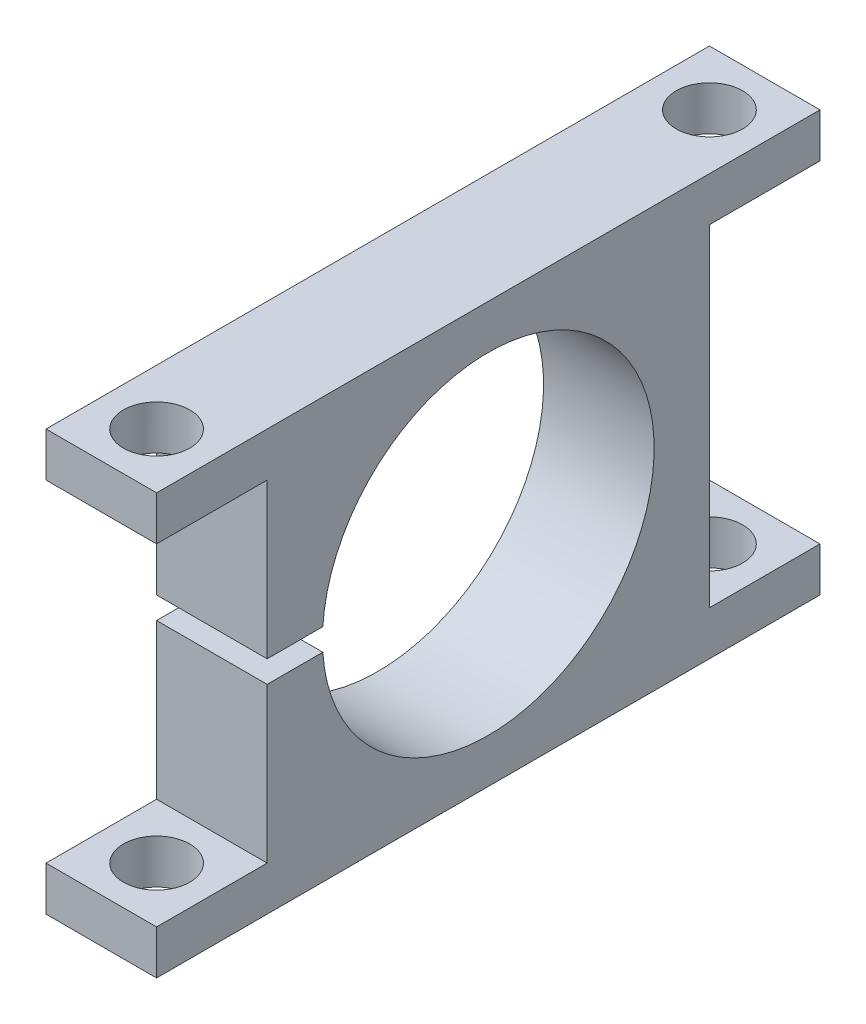
SolidWorks part; units mm, degrees
ref_plane "前视基准面" through (0, 0, 0) normal (0, 0, 1) x (1, 0, 0)
ref_plane "上视基准面" through (0, 0, 0) normal (0, 1, 0) x (1, 0, 0)
ref_plane "右视基准面" through (0, 0, 0) normal (1, 0, 0) x (0, 0, -1)
sketch "草图1" plane through (0, 0, 0) normal (1, 0, 0) x (0, 0, -1)
  line L1 (-10, -9.5) -> (10, -9.5)
  line L2 (10, -9.5) -> (10, 9.5)
  line L3 (10, 9.5) -> (-10, 9.5)
  line L4 (-10, -9.5) -> (-10, 9.5)
  line L5 (10, -9.5) -> (-10, 9.5) construction
  line L6 (10, 9.5) -> (-10, -9.5) construction
  circle A0 centre (0, 0) radius 7.5
  dimension "D1" = 20
  dimension "D2" = 15
  dimension "D3" = 19
extrude "凸台-拉伸3" add sketch "草图1" along normal blind 5
sketch "草图3" plane through (0, 0, 0) normal (-1, 0, 0) x (0, 0, 1)
  line L0 (10, 9.5) -> (15, 9.5)
  line L1 (15, 9.5) -> (15, 7.5)
  line L2 (15, 7.5) -> (10, 7.5)
  line L3 (10, 9.5) -> (10, -9.5) construction
  line L4 (10, 7.5) -> (10, 9.5)
  line L5 (10, -9.5) -> (15, -9.5)
  line L6 (15, -9.5) -> (15, -7.5)
  line L7 (15, -7.5) -> (10, -7.5)
  line L8 (10, -7.5) -> (10, -9.5)
  line L9 (-10, 9.5) -> (-15, 9.5)
  line L10 (-15, 9.5) -> (-15, 7.5)
  line L11 (-15, 7.5) -> (-10, 7.5)
  line L12 (-10, -9.5) -> (-10, 9.5) construction
  line L13 (-10, 7.5) -> (-10, 9.5)
  line L14 (-10, -9.5) -> (-15, -9.5)
  line L15 (-15, -9.5) -> (-15, -7.5)
  line L16 (-15, -7.5) -> (-10, -7.5)
  line L17 (-10, -7.5) -> (-10, -9.5)
  dimension "D1" = 2
  dimension "D2" = 5
  dimension "D3" = 2
  dimension "D4" = 5
extrude "凸台-拉伸4" add sketch "草图3" along normal blind 0.0001 and the other way blind 5
sketch "草图4" plane through (0, 9.5, 0) normal (0, 1, 0) x (1, 0, 0)
  circle A0 centre (2.5, -12.5) radius 1.5
extrude "切除-拉伸1" cut sketch "草图4" against normal through all
sketch "草图5" plane through (0, 9.5, 0) normal (0, 1, 0) x (1, 0, 0)
  circle A0 centre (2.5, 12.5) radius 1.5
extrude "切除-拉伸2" cut sketch "草图5" against normal through all
sketch "草图6" plane through (5, 0, 0) normal (1, 0, 0) x (0, 0, -1)
  line L1 (-4.833, -0.5) -> (-10.167, -0.5)
  line L2 (-4.833, -0.5) -> (-4.833, 0.5)
  line L3 (-4.833, 0.5) -> (-10.167, 0.5)
  line L4 (-10.167, -0.5) -> (-10.167, 0.5)
  line L5 (-4.833, -0.5) -> (-10.167, 0.5) construction
  line L6 (-4.833, 0.5) -> (-10.167, -0.5) construction
  circle A0 centre (0, 0) radius 7.5 construction
  point P0 (-7.5, 0)
  dimension "D1" = 1
extrude "切除-拉伸3" cut sketch "草图6" against normal through all
